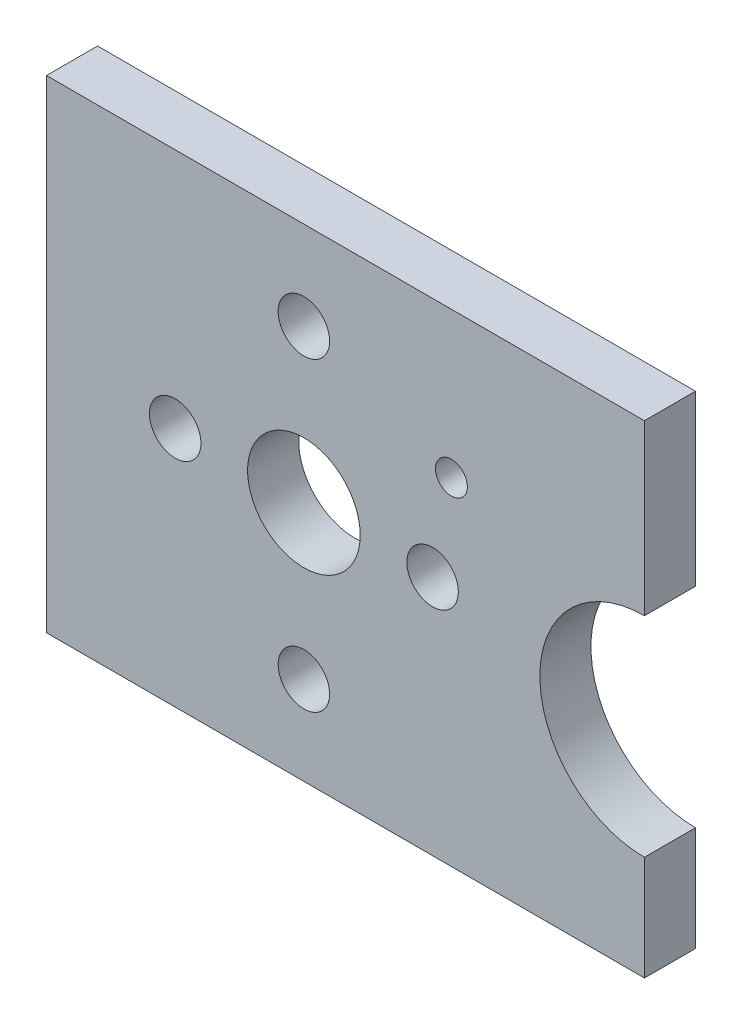
SolidWorks part; units mm, degrees
ref_plane "Front Plane" through (0, 0, 0) normal (0, 0, 1) x (1, 0, 0)
ref_plane "Top Plane" through (0, 0, 0) normal (0, 1, 0) x (1, 0, 0)
ref_plane "Right Plane" through (0, 0, 0) normal (1, 0, 0) x (0, 0, -1)
sketch "Sketch1" plane through (0, 0, 0) normal (0, 0, 1) x (1, 0, 0)
  line L0 (70, 15) -> (0, 15) construction
  line L1 (0, 0) -> (37.1667, 0)
  line L2 (0, 0) -> (0, 30)
  line L3 (0, 30) -> (37.1667, 30)
  line L4 (70, 0) -> (70, 30) construction
  line L5 (16, 24.5) -> (16, 15) construction
  line L6 (37.1667, 30) -> (37.1667, 0) construction
  line L7 (37.1667, 19.5) -> (37.1667, 30)
  line L8 (37.1667, 6.5) -> (37.1667, 0)
  line L9 (37.1667, 30) -> (70, 30) construction
  line L10 (37.1667, 0) -> (70, 0) construction
  circle A0 centre (55, 15) radius 2.4892 construction
  circle A1 centre (37.1667, 13) radius 1.4986 construction
  circle A2 centre (25.1698, 20.9334) radius 0.9906
  circle A3 centre (37.1667, 13) radius 11.4777 construction
  circle A4 centre (25.1698, 20.9334) radius 7.1501 construction
  circle A5 centre (55, 15) radius 12.827 construction
  circle A6 centre (16, 15) radius 14 construction
  circle A7 centre (37.1667, 13) radius 5.1181 construction
  circle A8 centre (16, 24.5) radius 1.6
  circle A9 centre (24, 15) radius 1.6
  circle A10 centre (16, 5.5) radius 1.6
  circle A11 centre (8, 15) radius 1.6
  arc A12 (37.1667, 19.5) -> (37.1667, 6.5) centre (37.1667, 13) ccw
  circle A13 centre (16, 15) radius 3.5
  point P7 (55, 15)
  point P8 (37.1667, 13)
  point P9 (25.1698, 20.9334)
  point P19 (16, 15)
  dimension "D6" = 4.9784
  dimension "D7" = 2.9972
  dimension "D8" = 1.9812
  dimension "D9" = 25.654
  dimension "D10" = 22.9553
  dimension "D11" = 14.3002
  dimension "D13" = 28
  dimension "D14" = 10.2362
  dimension "D17" = 3.2
  dimension "D18" = 9.5
  dimension "D20" = 6.5
  dimension "D21" = 7
  dimension "D1" = 17.9451
  dimension "D2" = 14.3828
  dimension "D3" = 30
  dimension "D4" = 70
  dimension "D5" = 15
  dimension "D12" = 10.922
  dimension "D15" = 16
  dimension "D16" = 13
  dimension "D19" = 8
extrude "Boss-Extrude2" add sketch "Sketch1" along normal blind 3.175
